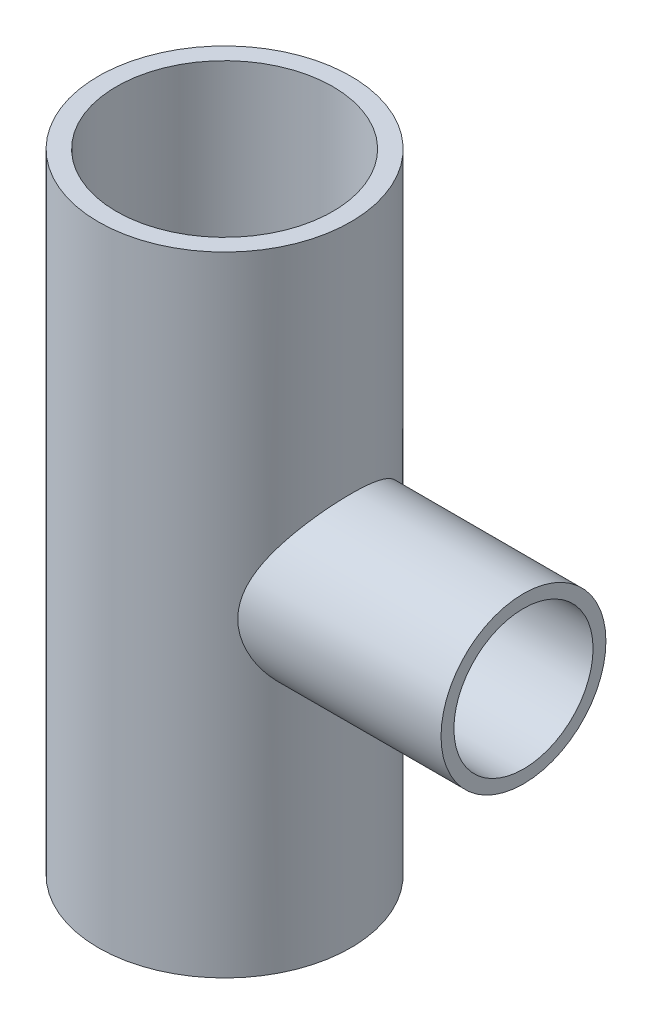
SolidWorks part; units mm, degrees
ref_plane "Front Plane" through (0, 0, 0) normal (0, 0, 1) x (1, 0, 0)
ref_plane "Top Plane" through (0, 0, 0) normal (0, 1, 0) x (1, 0, 0)
ref_plane "Right Plane" through (0, 0, 0) normal (1, 0, 0) x (0, 0, -1)
sketch "Sketch1" plane through (0, 0, 0) normal (0, 1, 0) x (1, 0, 0)
  circle A0 centre (0, 0) radius 21
  circle A1 centre (0, 0) radius 24.5
  dimension "D1" = 49
  dimension "D2" = 42
sketch "Sketch2" plane through (0, 0, 0) normal (0, 0, 1) x (1, 0, 0)
  line L0 (0, 0) -> (0, 122)
  line L1 (24.5, 0) -> (-24.5, 0) construction
  dimension "D1" = 122
sweep "Sweep2" add profiles "Sketch1" path "Sketch2"
sketch "Sketch5" plane through (0, 0, 0) normal (1, 0, 0) x (0, 0, -1)
  line L0 (0, -0.7103) -> (0, 60.2897)
  circle A0 centre (0, 60.2897) radius 16
  circle A1 centre (0, 60.2897) radius 13.5
extrude "Boss-Extrude3" add sketch "Sketch5" along normal blind 58 contours A1 | A0
